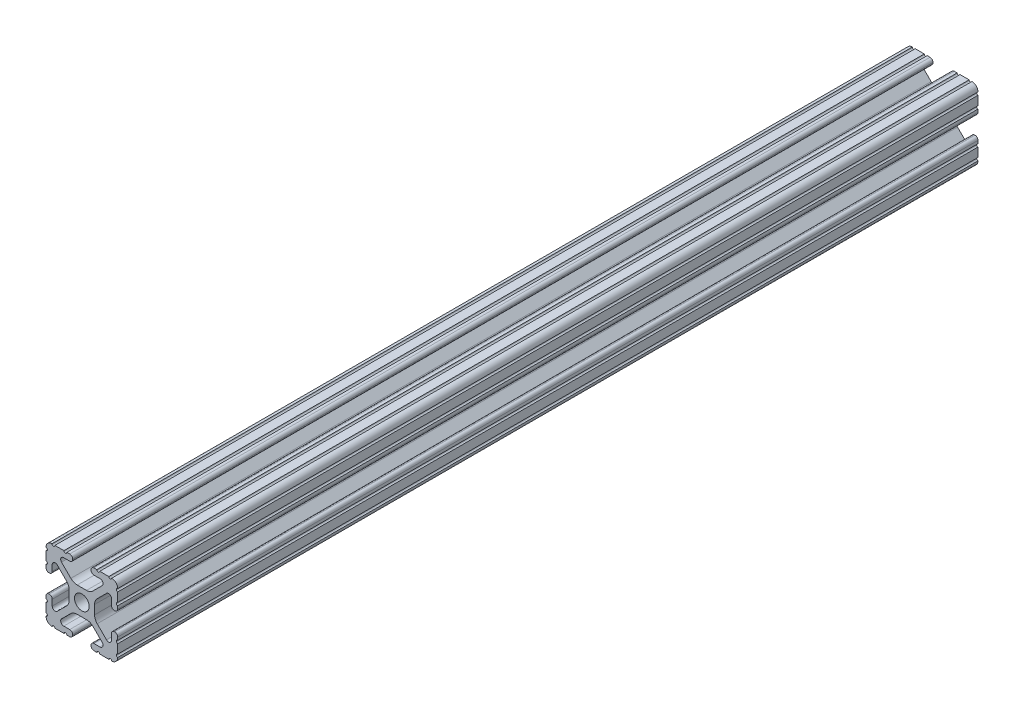
SolidWorks part; units mm, degrees
ref_plane "Front Plane" through (0, 0, 0) normal (0, 0, 1) x (1, 0, 0)
ref_plane "Top Plane" through (0, 0, 0) normal (0, 1, 0) x (1, 0, 0)
ref_plane "Right Plane" through (0, 0, 0) normal (1, 0, 0) x (0, 0, -1)
sketch "Sketch1" plane through (0, 0, 0) normal (0, 0, 1) x (1, 0, 0)
  line L0 (-7.207, 8.7244) -> (-3.8983, 5.4232)
  line L1 (-4.2875, 10.4902) -> (-6.4768, 10.4902)
  line L2 (-3.2385, 11.651) -> (-3.2385, 11.5392)
  line L3 (-5.3171, 12.7) -> (-4.2875, 12.7)
  line L4 (0, 13.4005) -> (0, -14.8534) construction
  line L5 (12.7, 0) -> (-13.9989, 0) construction
  line L6 (-9.5504, 12.7) -> (-6.3331, 12.7)
  line L7 (-12.7, 6.3331) -> (-12.7, 9.5504)
  line L8 (-12.7, 4.2875) -> (-12.7, 5.3171)
  line L9 (-11.5392, 3.2385) -> (-11.651, 3.2385)
  line L10 (-10.4902, 6.4021) -> (-10.4902, 4.2875)
  line L11 (-5.441, 3.8408) -> (-8.7371, 7.1294)
  line L12 (-4.5085, -1.5932) -> (-4.5085, 1.5932)
  line L13 (-1.7093, -4.4958) -> (1.7093, -4.4958)
  line L14 (3.9523, -5.4237) -> (7.1797, -8.6452)
  line L15 (6.4164, -10.4902) -> (4.2875, -10.4902)
  line L16 (3.2385, -11.5392) -> (3.2385, -11.651)
  line L17 (4.2875, -12.7) -> (5.3171, -12.7)
  line L18 (6.3331, -12.7) -> (9.5504, -12.7)
  line L19 (12.7, -9.5504) -> (12.7, -6.3331)
  line L20 (12.7, -5.3171) -> (12.7, -4.2875)
  line L21 (11.651, -3.2385) -> (11.5392, -3.2385)
  line L22 (10.4902, -4.2875) -> (10.4902, -6.4021)
  line L23 (8.7371, -7.1294) -> (5.441, -3.8408)
  line L24 (4.5085, -1.5932) -> (4.5085, 1.5932)
  line L25 (5.441, 3.8408) -> (8.7371, 7.1294)
  line L26 (10.4902, 6.4021) -> (10.4902, 4.2875)
  line L27 (11.5392, 3.2385) -> (11.651, 3.2385)
  line L28 (12.7, 4.2875) -> (12.7, 5.3171)
  line L29 (12.7, 6.3331) -> (12.7, 9.5504)
  line L30 (9.5504, 12.7) -> (6.3331, 12.7)
  line L31 (5.3171, 12.7) -> (4.2875, 12.7)
  line L32 (3.2385, 11.651) -> (3.2385, 11.5392)
  line L33 (4.2875, 10.4902) -> (6.4768, 10.4902)
  line L34 (7.207, 8.7244) -> (3.8983, 5.4232)
  line L35 (1.6558, 4.4958) -> (-1.6558, 4.4958)
  line L36 (-8.7371, -7.1294) -> (-5.441, -3.8408)
  line L37 (-10.4902, -4.2875) -> (-10.4902, -6.4021)
  line L38 (-11.651, -3.2385) -> (-11.5392, -3.2385)
  line L39 (-12.7, -5.3171) -> (-12.7, -4.2875)
  line L40 (-12.7, -9.5504) -> (-12.7, -6.3331)
  line L41 (-6.3331, -12.7) -> (-9.5504, -12.7)
  line L42 (-4.2875, -12.7) -> (-5.3171, -12.7)
  line L43 (-3.2385, -11.5392) -> (-3.2385, -11.651)
  line L44 (-6.4164, -10.4902) -> (-4.2875, -10.4902)
  line L45 (-3.9523, -5.4237) -> (-7.1797, -8.6452)
  arc A0 (-7.207, 8.7244) -> (-6.4768, 10.4902) centre (-6.4768, 9.4563) cw
  arc A1 (-3.2385, 11.5392) -> (-4.2875, 10.4902) centre (-4.2875, 11.5392) cw
  arc A2 (-4.2875, 12.7) -> (-3.2385, 11.651) centre (-4.2875, 11.651) cw
  arc A3 (-5.3171, 12.7) -> (-6.3331, 12.7) centre (-5.8251, 12.7) cw
  arc A4 (-9.5504, 12.7) -> (-10.5664, 12.6998) centre (-10.0584, 12.7) cw
  arc A5 (-12.6998, 10.5664) -> (-10.5664, 12.6998) centre (-10.5918, 10.5918) cw
  arc A6 (-12.6998, 10.5664) -> (-12.7, 9.5504) centre (-12.7, 10.0584) cw
  arc A7 (-12.7, 6.3331) -> (-12.7, 5.3171) centre (-12.7, 5.8251) cw
  arc A8 (-11.651, 3.2385) -> (-12.7, 4.2875) centre (-11.651, 4.2875) cw
  arc A9 (-10.4902, 4.2875) -> (-11.5392, 3.2385) centre (-11.5392, 4.2875) cw
  circle A10 centre (0, 0) radius 2.6035
  arc A11 (-10.4902, 6.4021) -> (-8.7371, 7.1294) centre (-9.4628, 6.4021) cw
  arc A12 (-5.441, 3.8408) -> (-4.5085, 1.5932) centre (-7.6835, 1.5932) cw
  arc A13 (-4.5085, -1.5932) -> (-5.441, -3.8408) centre (-7.6835, -1.5932) cw
  arc A14 (-8.7371, -7.1294) -> (-10.4902, -6.4021) centre (-9.4628, -6.4021) cw
  arc A15 (-1.7093, -4.4958) -> (-3.9523, -5.4237) centre (-1.7093, -7.6708) ccw
  arc A16 (3.9523, -5.4237) -> (1.7093, -4.4958) centre (1.7093, -7.6708) ccw
  arc A17 (6.4164, -10.4902) -> (7.1797, -8.6452) centre (6.4164, -9.4098) ccw
  arc A18 (4.2875, -10.4902) -> (3.2385, -11.5392) centre (4.2875, -11.5392) ccw
  arc A19 (3.2385, -11.651) -> (4.2875, -12.7) centre (4.2875, -11.651) ccw
  arc A20 (6.3331, -12.7) -> (5.3171, -12.7) centre (5.8251, -12.7) ccw
  arc A21 (10.5664, -12.6998) -> (9.5504, -12.7) centre (10.0584, -12.7) ccw
  arc A22 (10.5664, -12.6998) -> (12.6998, -10.5664) centre (10.5918, -10.5918) ccw
  arc A23 (12.7, -9.5504) -> (12.6998, -10.5664) centre (12.7, -10.0584) ccw
  arc A24 (12.7, -5.3171) -> (12.7, -6.3331) centre (12.7, -5.8251) ccw
  arc A25 (12.7, -4.2875) -> (11.651, -3.2385) centre (11.651, -4.2875) ccw
  arc A26 (11.5392, -3.2385) -> (10.4902, -4.2875) centre (11.5392, -4.2875) ccw
  arc A27 (8.7371, -7.1294) -> (10.4902, -6.4021) centre (9.4628, -6.4021) ccw
  arc A28 (4.5085, -1.5932) -> (5.441, -3.8408) centre (7.6835, -1.5932) ccw
  arc A29 (5.441, 3.8408) -> (4.5085, 1.5932) centre (7.6835, 1.5932) ccw
  arc A30 (10.4902, 6.4021) -> (8.7371, 7.1294) centre (9.4628, 6.4021) ccw
  arc A31 (10.4902, 4.2875) -> (11.5392, 3.2385) centre (11.5392, 4.2875) ccw
  arc A32 (11.651, 3.2385) -> (12.7, 4.2875) centre (11.651, 4.2875) ccw
  arc A33 (12.7, 6.3331) -> (12.7, 5.3171) centre (12.7, 5.8251) ccw
  arc A34 (12.6998, 10.5664) -> (12.7, 9.5504) centre (12.7, 10.0584) ccw
  arc A35 (12.6998, 10.5664) -> (10.5664, 12.6998) centre (10.5918, 10.5918) ccw
  arc A36 (9.5504, 12.7) -> (10.5664, 12.6998) centre (10.0584, 12.7) ccw
  arc A37 (5.3171, 12.7) -> (6.3331, 12.7) centre (5.8251, 12.7) ccw
  arc A38 (4.2875, 12.7) -> (3.2385, 11.651) centre (4.2875, 11.651) ccw
  arc A39 (3.2385, 11.5392) -> (4.2875, 10.4902) centre (4.2875, 11.5392) ccw
  arc A40 (7.207, 8.7244) -> (6.4768, 10.4902) centre (6.4768, 9.4563) ccw
  arc A41 (1.6558, 4.4958) -> (3.8983, 5.4232) centre (1.6558, 7.6708) ccw
  arc A42 (-1.6558, 4.4958) -> (-3.8983, 5.4232) centre (-1.6558, 7.6708) cw
  arc A43 (-11.5392, -3.2385) -> (-10.4902, -4.2875) centre (-11.5392, -4.2875) cw
  arc A44 (-12.7, -4.2875) -> (-11.651, -3.2385) centre (-11.651, -4.2875) cw
  arc A45 (-12.7, -5.3171) -> (-12.7, -6.3331) centre (-12.7, -5.8251) cw
  arc A46 (-12.7, -9.5504) -> (-12.6998, -10.5664) centre (-12.7, -10.0584) cw
  arc A47 (-10.5664, -12.6998) -> (-12.6998, -10.5664) centre (-10.5918, -10.5918) cw
  arc A48 (-10.5664, -12.6998) -> (-9.5504, -12.7) centre (-10.0584, -12.7) cw
  arc A49 (-6.3331, -12.7) -> (-5.3171, -12.7) centre (-5.8251, -12.7) cw
  arc A50 (-3.2385, -11.651) -> (-4.2875, -12.7) centre (-4.2875, -11.651) cw
  arc A51 (-4.2875, -10.4902) -> (-3.2385, -11.5392) centre (-4.2875, -11.5392) cw
  arc A52 (-6.4164, -10.4902) -> (-7.1797, -8.6452) centre (-6.4164, -9.4098) cw
  dimension "D1" = 5.207
  dimension "D9" = 14.859
  dimension "D2" = 25.4
  dimension "D3" = 12.7
  dimension "D4" = 6.477
  dimension "D5" = 8.2042
  dimension "D6" = 9.017
  dimension "D8" = 2.2098
  dimension "D10" = 2.2098
extrude "Extrude1" add sketch "Sketch1" against normal blind 304.8
